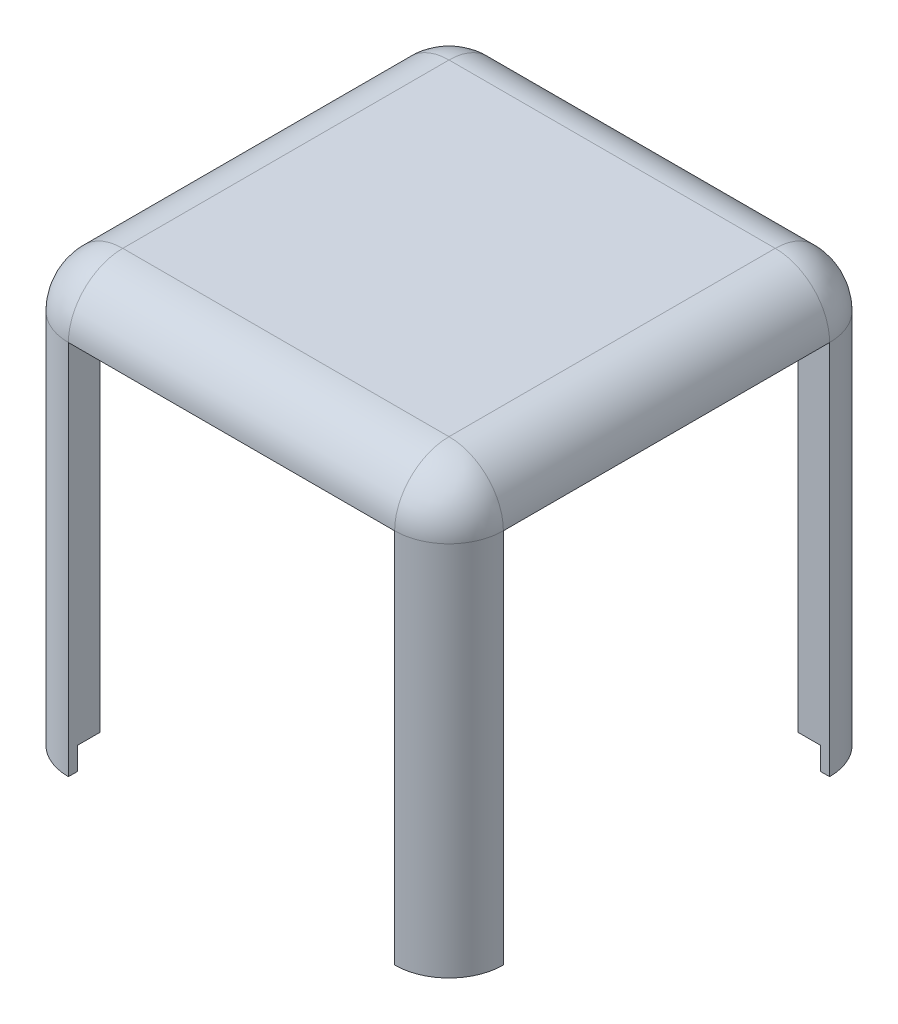
SolidWorks part; units mm, degrees
ref_plane "前视基准面" through (0, 0, 0) normal (0, 0, 1) x (1, 0, 0)
ref_plane "上视基准面" through (0, 0, 0) normal (0, 1, 0) x (1, 0, 0)
ref_plane "右视基准面" through (0, 0, 0) normal (1, 0, 0) x (0, 0, -1)
sketch "草图1" plane through (0, 0, 0) normal (0, 1, 0) x (1, 0, 0)
  line L1 (-18, -24) -> (18, -24)
  line L2 (-24, -18) -> (-24, 18)
  line L3 (-18, 24) -> (18, 24)
  line L4 (24, -18) -> (24, 18)
  line L5 (-24, -24) -> (24, 24) construction
  line L6 (-24, 24) -> (24, -24) construction
  arc A0 (18, 24) -> (24, 18) centre (18, 18) cw
  arc A1 (24, -18) -> (18, -24) centre (18, -18) cw
  arc A2 (-18, -24) -> (-24, -18) centre (-18, -18) cw
  arc A3 (-24, 18) -> (-18, 24) centre (-18, 18) cw
  point P0 (0, 0)
  dimension "D3" = 6
  dimension "D1" = 48
  dimension "D2" = 48
extrude "凸台-拉伸1" add sketch "草图1" along normal blind 51.5 contours L3 A0 L4 A1 L1 A2 L2 A3
fillet "圆角2" radius 6 8 edges at (0, 51.5, -24) (22.2426, 51.5, -22.2426) (24, 51.5, 0) (22.2426, 51.5, 22.2426) (0, 51.5, 24) (-22.2426, 51.5, 22.2426) (-24, 51.5, 0) (-22.2426, 51.5, -22.2426)
sketch "草图2" plane through (0, 0, 0) normal (0, -1, 0) x (1, 0, 0)
  line L1 (-20.5, -20.5) -> (20.5, -20.5)
  line L2 (-20.5, -20.5) -> (-20.5, 20.5)
  line L3 (-20.5, 20.5) -> (20.5, 20.5)
  line L4 (20.5, -20.5) -> (20.5, 20.5)
  line L5 (-20.5, -20.5) -> (20.5, 20.5) construction
  line L6 (-20.5, 20.5) -> (20.5, -20.5) construction
  point P0 (0, 0)
  dimension "D1" = 41
  dimension "D2" = 41
extrude "切除-拉伸1" cut sketch "草图2" against normal blind 48.5
sketch "草图3" plane through (0, 0, -24) normal (0, 0, -1) x (-1, 0, 0)
  line L0 (-18, 45.5) -> (-18, 0)
  line L1 (-18, 0) -> (18, 0)
  line L2 (18, 0) -> (18, 45.5)
  line L3 (18, 45.5) -> (-18, 45.5)
extrude "切除-拉伸2" cut sketch "草图3" against normal blind 54
sketch "草图4" plane through (-24, 0, 0) normal (-1, 0, 0) x (0, 0, 1)
  line L0 (-18, 45.5) -> (-18, 0)
  line L1 (-18, 0) -> (18, 0)
  line L2 (18, 0) -> (18, 45.5)
  line L3 (18, 45.5) -> (-18, 45.5)
extrude "切除-拉伸3" cut sketch "草图4" against normal blind 54
sketch "草图5" plane through (0, 0, 0) normal (0, -1, 0) x (1, 0, 0)
  line L1 (-17.5, -23) -> (17.5, -23)
  line L2 (-23, -17.5) -> (-23, 17.5)
  line L3 (-17.5, 23) -> (17.5, 23)
  line L4 (23, -17.5) -> (23, 17.5)
  line L5 (-23, -23) -> (23, 23) construction
  line L6 (-23, 23) -> (23, -23) construction
  arc A0 (-23, -17.5) -> (-17.5, -23) centre (-17.5, -17.5) ccw
  arc A1 (17.5, -23) -> (23, -17.5) centre (17.5, -17.5) ccw
  arc A2 (23, 17.5) -> (17.5, 23) centre (17.5, 17.5) ccw
  arc A3 (-17.5, 23) -> (-23, 17.5) centre (-17.5, 17.5) ccw
  point P0 (0, 0)
  dimension "D3" = 5.5
  dimension "D1" = 46
  dimension "D2" = 46
extrude "切除-拉伸4" cut sketch "草图5" against normal blind 6.5
sketch "草图8" plane through (0, 0, 0) normal (0, -1, 0) x (1, 0, 0)
  line L0 (18, -22.9772) -> (18, -24) construction
  line L1 (24, -18) -> (22.9772, -18) construction
  line L2 (22.9772, 18) -> (24, 18) construction
  line L3 (18, 24) -> (18, 22.9772) construction
  line L4 (-18, 22.9772) -> (-18, 24) construction
  line L5 (-24, 18) -> (-22.9772, 18) construction
  line L6 (-22.9772, -18) -> (-24, -18) construction
  line L7 (-18, -24) -> (-18, -22.9772) construction
  line L8 (18, -22.9772) -> (18, -24)
  line L9 (24, -18) -> (22.9772, -18)
  line L10 (22.9772, 18) -> (24, 18)
  line L11 (18, 24) -> (18, 22.9772)
  line L12 (-18, 22.9772) -> (-18, 24)
  line L13 (-24, 18) -> (-22.9772, 18)
  line L14 (-22.9772, -18) -> (-24, -18)
  line L15 (-18, -24) -> (-18, -22.9772)
  arc A0 (18, -22.9772) -> (22.9772, -18) centre (17.5, -17.5) ccw construction
  arc A1 (18, -24) -> (24, -18) centre (18, -18) ccw construction
  arc A2 (22.9772, 18) -> (18, 22.9772) centre (17.5, 17.5) ccw construction
  arc A3 (24, 18) -> (18, 24) centre (18, 18) ccw construction
  arc A4 (-18, 22.9772) -> (-22.9772, 18) centre (-17.5, 17.5) ccw construction
  arc A5 (-18, 24) -> (-24, 18) centre (-18, 18) ccw construction
  arc A6 (-22.9772, -18) -> (-18, -22.9772) centre (-17.5, -17.5) ccw construction
  arc A7 (-24, -18) -> (-18, -24) centre (-18, -18) ccw construction
  arc A8 (18, -22.9772) -> (22.9772, -18) centre (17.5, -17.5) ccw
  arc A9 (18, -24) -> (24, -18) centre (18, -18) ccw
  arc A10 (22.9772, 18) -> (18, 22.9772) centre (17.5, 17.5) ccw
  arc A11 (24, 18) -> (18, 24) centre (18, 18) ccw
  arc A12 (-18, 22.9772) -> (-22.9772, 18) centre (-17.5, 17.5) ccw
  arc A13 (-18, 24) -> (-24, 18) centre (-18, 18) ccw
  arc A14 (-22.9772, -18) -> (-18, -22.9772) centre (-17.5, -17.5) ccw
  arc A15 (-24, -18) -> (-18, -24) centre (-18, -18) ccw
extrude "切除-拉伸5" cut sketch "草图8" against normal blind 4
